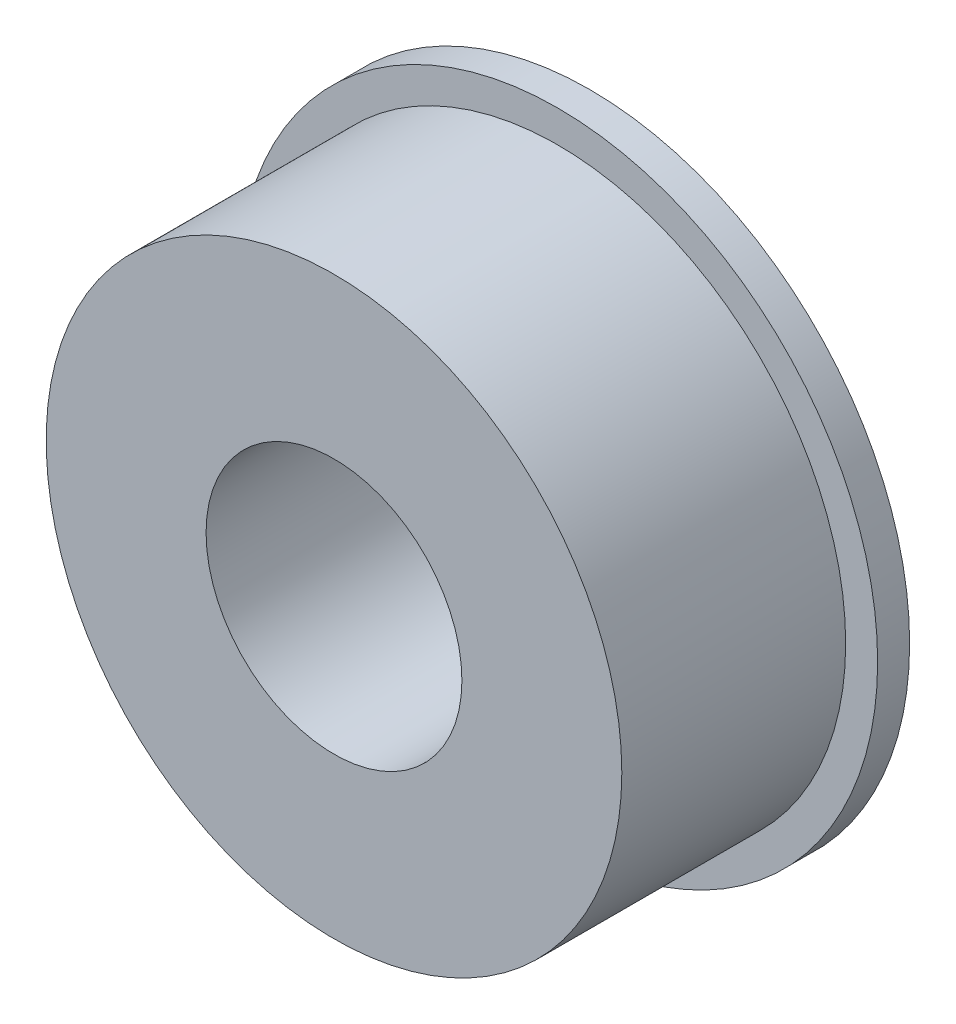
SolidWorks part; units mm, degrees
ref_plane "Front Plane" through (0, 0, 0) normal (0, 0, 1) x (1, 0, 0)
ref_plane "Top Plane" through (0, 0, 0) normal (0, 1, 0) x (1, 0, 0)
ref_plane "Right Plane" through (0, 0, 0) normal (1, 0, 0) x (0, 0, -1)
sketch "Sketch2" plane through (0, 0, 0) normal (0, 0, 1) x (1, 0, 0)
  circle A0 centre (0, 0) radius 15.875
  dimension "D1" = 31.75
extrude "Boss-Extrude1" add sketch "Sketch2" along normal blind 1.5875
sketch "Sketch3" plane through (0, 0, 1.5875) normal (0, 0, 1) x (1, 0, 0)
  circle A0 centre (0, 0) radius 14.2875
  dimension "D1" = 28.575
extrude "Boss-Extrude2" add sketch "Sketch3" along normal blind 11.1125
sketch "Sketch4" plane through (0, 0, 12.7) normal (0, 0, 1) x (1, 0, 0)
  circle A0 centre (0, 0) radius 6.35
  dimension "D1" = 12.7
extrude "Cut-Extrude1" cut sketch "Sketch4" against normal through all
